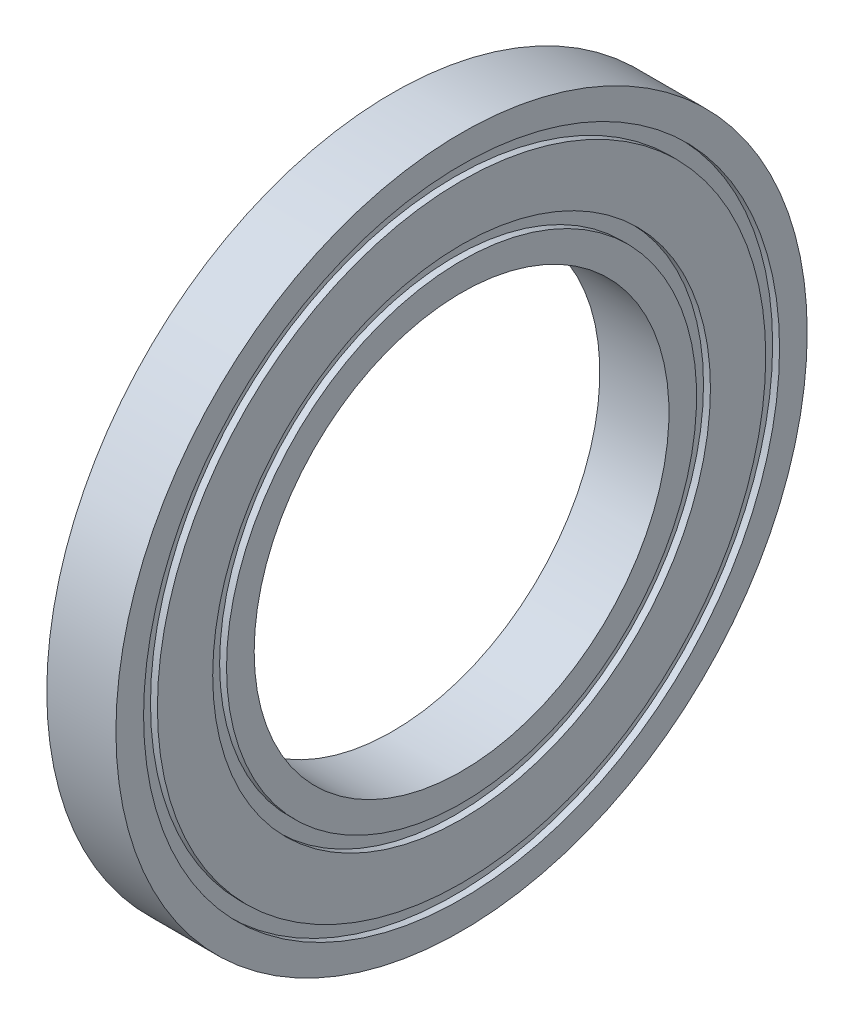
SolidWorks part; units mm, degrees
ref_plane "Front Plane" through (0, 0, 0) normal (0, 0, 1) x (1, 0, 0)
ref_plane "Top Plane" through (0, 0, 0) normal (0, 1, 0) x (1, 0, 0)
ref_plane "Right Plane" through (0, 0, 0) normal (1, 0, 0) x (0, 0, -1)
sketch "Sketch1" plane through (0, 0, 0) normal (0, 0, 1) x (1, 0, 0)
  line L0 (0, 0) -> (0, 15) construction
  line L1 (0, 15) -> (0, 25) construction
  line L2 (-2.5, 25) -> (2.5, 25)
  line L3 (2.5, 25) -> (2.5, 23)
  line L4 (2.5, 23) -> (2, 23)
  line L5 (2, 23) -> (2, 22)
  line L6 (2, 22) -> (2.5, 22)
  line L7 (2.5, 22) -> (2.5, 18)
  line L8 (2.5, 20) -> (0, 20) construction
  line L9 (2, 18) -> (2.5, 18)
  line L10 (2, 17) -> (2, 18)
  line L11 (2.5, 17) -> (2, 17)
  line L12 (2.5, 15) -> (2.5, 17)
  line L13 (-2.5, 15) -> (2.5, 15)
  line L14 (-2.5, 15) -> (-2.5, 17)
  line L15 (-2.5, 17) -> (-2, 17)
  line L16 (-2, 17) -> (-2, 18)
  line L17 (-2, 18) -> (-2.5, 18)
  line L18 (-2.5, 22) -> (-2.5, 18)
  line L19 (-2, 22) -> (-2.5, 22)
  line L20 (-2, 23) -> (-2, 22)
  line L21 (-2.5, 23) -> (-2, 23)
  line L22 (-2.5, 25) -> (-2.5, 23)
  line L23 (0, 0) -> (13.2088, 0) construction
  dimension "D1" = 5
  dimension "D2" = 2
  dimension "D3" = 0.5
  dimension "D4" = 5
  dimension "D5" = 2
  dimension "D6" = 2
  dimension "D7" = 20
revolve "Revolve1" add sketch "Sketch1" angle 360 about L23
